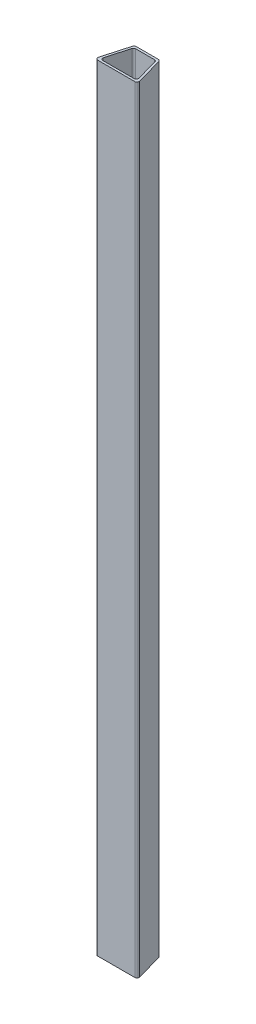
SolidWorks part; units mm, degrees
ref_plane "Front Plane" through (0, 0, 0) normal (0, 0, 1) x (1, 0, 0)
ref_plane "Top Plane" through (0, 0, 0) normal (0, 1, 0) x (1, 0, 0)
ref_plane "Right Plane" through (0, 0, 0) normal (1, 0, 0) x (0, 0, -1)
sketch "Sketch1" plane through (0, 0, 0) normal (0, 1, 0) x (1, 0, 0)
  line L1 (-8.3599, -7) -> (8.3599, -7)
  line L5 (5.9476, 6.2707) -> (9.3226, -5.7293)
  line L6 (-4.9849, 7) -> (4.9849, 7)
  line L7 (-5.9476, 6.2707) -> (-9.3226, -5.7293)
  line L8 (-7.0399, -6) -> (7.0399, -6)
  line L9 (5.19, 5.2707) -> (8.0025, -4.7293)
  line L10 (-4.2274, 6) -> (4.2274, 6)
  line L11 (-5.19, 5.2707) -> (-8.0025, -4.7293)
  line L12 (-4.9849, 6) -> (-8.3599, -6) construction
  line L13 (-8.3599, -6) -> (8.3599, -6) construction
  line L14 (4.9849, 6) -> (8.3599, -6) construction
  line L15 (-4.9849, 6) -> (4.9849, 6) construction
  arc A4 (8.3599, -7) -> (9.3226, -5.7293) centre (8.3599, -6) ccw
  arc A5 (4.9849, 7) -> (5.9476, 6.2707) centre (4.9849, 6) cw
  arc A6 (-4.9849, 7) -> (-5.9476, 6.2707) centre (-4.9849, 6) ccw
  arc A7 (-8.3599, -7) -> (-9.3226, -5.7293) centre (-8.3599, -6) cw
  arc A8 (5.19, 5.2707) -> (4.2274, 6) centre (4.2274, 5) ccw
  arc A9 (-4.2274, 6) -> (-5.19, 5.2707) centre (-4.2274, 5) ccw
  arc A11 (8.0025, -4.7293) -> (7.0399, -6) centre (7.0399, -5) cw
  arc A12 (-8.0025, -4.7293) -> (-7.0399, -6) centre (-7.0399, -5) ccw
  arc A13 (-8.3599, -6) -> (-8.3599, -6) centre (-8.3599, -6) cw construction
  arc A14 (8.3599, -6) -> (8.3599, -6) centre (8.3599, -6) ccw construction
  arc A15 (4.9849, 6) -> (4.9849, 6) centre (4.9849, 6) cw construction
  arc A16 (-4.9849, 6) -> (-4.9849, 6) centre (-4.9849, 6) ccw construction
  dimension "D2" = 1
  dimension "D1" = 1
extrude "Boss-Extrude1" add sketch "Sketch1" along normal blind 350
